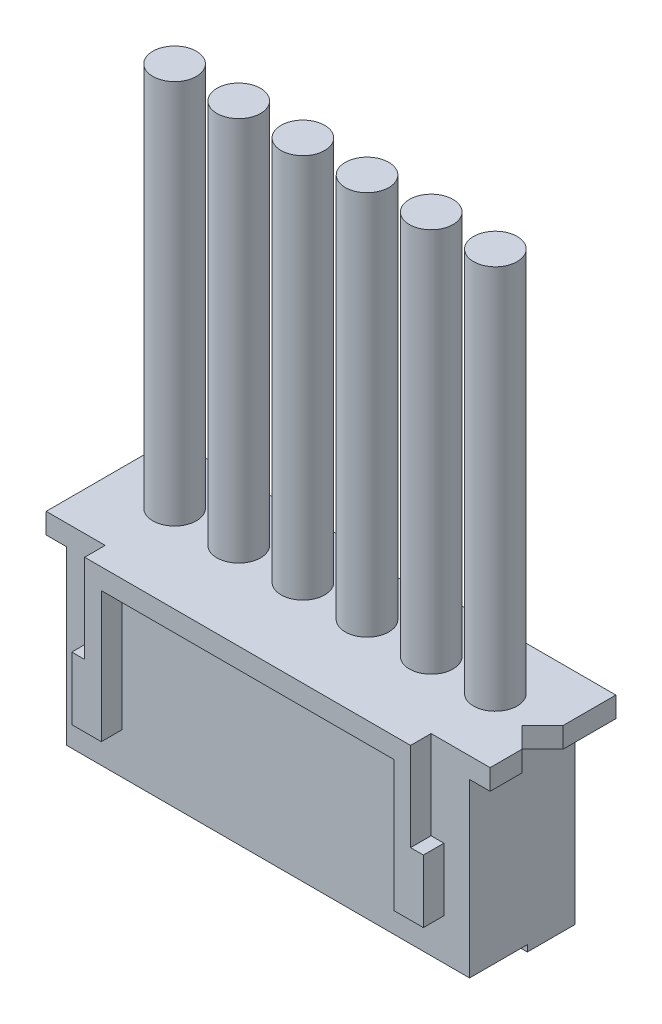
SolidWorks part; units mm, degrees
ref_plane "Plan de face" through (0, 0, 0) normal (0, 0, 1) x (1, 0, 0)
ref_plane "Plan de dessus" through (0, 0, 0) normal (0, 1, 0) x (1, 0, 0)
ref_plane "Plan de droite" through (0, 0, 0) normal (1, 0, 0) x (0, 0, -1)
sketch "Esquisse1" plane through (0, 0, 0) normal (0, 1, 0) x (1, 0, 0)
  line L1 (-7.85, 2.05) -> (7.85, 2.05)
  line L2 (-7.85, 2.05) -> (-7.85, -2.05)
  line L3 (-7.85, -2.05) -> (7.85, -2.05)
  line L4 (7.85, 2.05) -> (7.85, -2.05)
  point P4 (0, 2.05)
  point P6 (-7.85, 0)
  dimension "D1" = 15.7
  dimension "D2" = 4.1
extrude "Boss.-Extru.1" add sketch "Esquisse1" along normal blind 7.75
sketch "Esquisse2" plane through (0, 0, 0) normal (0, 1, 0) x (1, 0, 0)
  line L1 (-7.85, -2.05) -> (7.85, -2.05)
  line L2 (-7.85, -2.05) -> (-7.85, 0.2)
  line L3 (-7.85, 0.2) -> (7.85, 0.2)
  line L4 (7.85, -2.05) -> (7.85, 0.2)
  line L5 (7.85, -2.05) -> (7.85, 2.05) construction
  dimension "D1" = 2.25
extrude "Enlèv. mat.-Extru.1" cut sketch "Esquisse2" along normal blind 0.25
sketch "Esquisse3" plane through (0, 7.75, 0) normal (0, 1, 0) x (1, 0, 0)
  line L0 (-7.85, -2.05) -> (7.85, -2.05) construction
  line L1 (-8.65, 2.85) -> (8.65, 2.85)
  line L2 (-8.65, 2.85) -> (-8.65, -2.05)
  line L3 (-8.65, -2.05) -> (8.65, -2.05)
  line L4 (8.65, 2.85) -> (8.65, -2.05)
  line L5 (-7.85, 2.05) -> (-7.85, -2.05) construction
  point P5 (0, 2.85)
  dimension "D1" = 0.8
  dimension "D2" = 4.9
extrude "Boss.-Extru.2" add sketch "Esquisse3" against normal blind 0.8
sketch "Esquisse8" plane through (0, 7.75, 0) normal (0, 1, 0) x (1, 0, 0)
  line L0 (-0.8, 2.85) -> (0, 2.05)
  line L1 (8.65, 2.85) -> (-8.65, 2.85) construction
  line L2 (0, 2.05) -> (0.8, 2.85)
  line L3 (0.8, 2.85) -> (-0.8, 2.85)
  line L4 (7.85, 2.05) -> (-7.85, 2.05) construction
  line L6 (8.65, 0.8) -> (7.85, 0)
  line L7 (8.65, -2.05) -> (8.65, 2.85) construction
  line L8 (7.85, 0) -> (8.65, -0.8)
  line L9 (8.65, 0.8) -> (8.65, -0.8)
  line L10 (7.85, -2.05) -> (7.85, 2.05) construction
extrude "Enlèv. mat.-Extru.4" cut sketch "Esquisse8" against normal through all
sketch "Esquisse4" plane through (0, 0, 2.05) normal (0, 0, 1) x (1, 0, 0)
  line L0 (0, 0) -> (0, 8.5573) construction
  line L1 (7.85, 0) -> (-7.85, 0) construction
  line L17 (5.7, 6.95) -> (-5.7, 6.95)
  line L18 (-5.7, 6.95) -> (-5.7, 1.85)
  line L19 (-5.7, 1.85) -> (-6.85, 1.85)
  line L20 (-6.85, 1.85) -> (-6.85, 4.3)
  line L21 (-6.85, 4.3) -> (-6.35, 4.3)
  line L23 (-8.65, 7.75) -> (8.65, 7.75) construction
  line L24 (-6.35, 7.75) -> (6.35, 7.75)
  line L26 (6.85, 4.3) -> (6.35, 4.3)
  line L27 (6.85, 1.85) -> (6.85, 4.3)
  line L28 (5.7, 1.85) -> (6.85, 1.85)
  line L29 (5.7, 6.95) -> (5.7, 1.85)
  line L30 (-8.65, 6.95) -> (-7.85, 6.95) construction
  line L31 (-7.85, 6.95) -> (-7.85, 0.25) construction
  line L32 (-6.35, 7.75) -> (-6.35, 4.3)
  line L33 (6.35, 7.75) -> (6.35, 4.3)
  point P15 (0, 7.75)
  point P20 (0, 6.95)
  point P22 (0, 7.75)
  dimension "D1" = 5.1
  dimension "D2" = 1.15
  dimension "D3" = 2.45
  dimension "D4" = 1.5
  dimension "D6" = 1
extrude "Boss.-Extru.3" add sketch "Esquisse4" along normal blind 0.8
sketch "Esquisse5" plane through (0, 0, 0) normal (0, 1, 0) x (1, 0, 0)
  line L0 (-6.915, 2.05) -> (-6.7, 1.25)
  line L1 (7.85, 2.05) -> (0, 2.05) construction
  line L2 (-6.7, 1.25) -> (-5.8, 1.25)
  line L3 (-5.8, 1.25) -> (-5.585, 2.05)
  line L4 (7.85, 2.05) -> (-7.85, 2.05) construction
  line L5 (-5.585, 2.05) -> (-6.915, 2.05)
  line L6 (-6.25, 1.25) -> (6.25, 1.25) construction
  point P4 (-6.25, 1.25)
  point P9 (-6.25, 2.05)
  point P10 (0, 1.25)
  dimension "D1" = 0.9
  dimension "D2" = 1.33
  dimension "D3" = 0.8
  dimension "D4" = 12.5
extrude "Enlèv. mat.-Extru.2" cut sketch "Esquisse5" along normal blind 2.9
sketch "Esquisse6" plane through (0, 0.25, 0) normal (0, -1, 0) x (1, 0, 0)
  line L0 (-6.25, 0.17) -> (6.25, 0.17) construction
  line L1 (-6.625, 0.92) -> (-5.875, 0.92)
  line L2 (-6.625, 0.92) -> (-6.625, 0.17)
  line L3 (-6.625, 0.17) -> (-5.875, 0.17)
  line L4 (-5.875, 0.92) -> (-5.875, 0.17)
  line L6 (-7.85, 2.05) -> (7.85, 2.05) construction
  point P6 (0, 0.17)
  dimension "D1" = 0.75
  dimension "D2" = 12.5
  dimension "D3" = 1.88
extrude "Enlèv. mat.-Extru.3" cut sketch "Esquisse6" against normal blind 0.5
sketch "Esquisse7" plane through (0, 7.75, 0) normal (0, 1, 0) x (1, 0, 0)
  line L0 (-6.25, 0.5547) -> (6.25, 0.5547) construction
  circle A0 centre (-6.25, 0.5547) radius 0.85
  point P2 (0, 0.5547)
  dimension "D2" = 1.7
  dimension "D1" = 12.5
extrude "Boss.-Extru.4" add sketch "Esquisse7" along normal blind 15 contours A0
pattern_linear "Répétition linéaire2" count 6 spacing 2.5 along (1, 0, 0) of "Boss.-Extru.4", "Enlèv. mat.-Extru.2", "Enlèv. mat.-Extru.3"
equation "\"conductors\"= 6"
equation "\"D2@Esquisse6\"=\"first_to_last_conductor_spacing\""
equation "\"D1@Esquisse7\"=\"first_to_last_conductor_spacing\""
equation "\"first_to_last_conductor_spacing\"= ( \"conductors\" - 1 ) * 2.5"
equation "\"D4@Esquisse5\"=\"first_to_last_conductor_spacing\""
equation "\"B\"= \"conductors\" * 2.5 + .7"
equation "\"D1@Répétition linéaire2\"=\"conductors\""
equation "\"D1@Esquisse1\"=\"B\""
